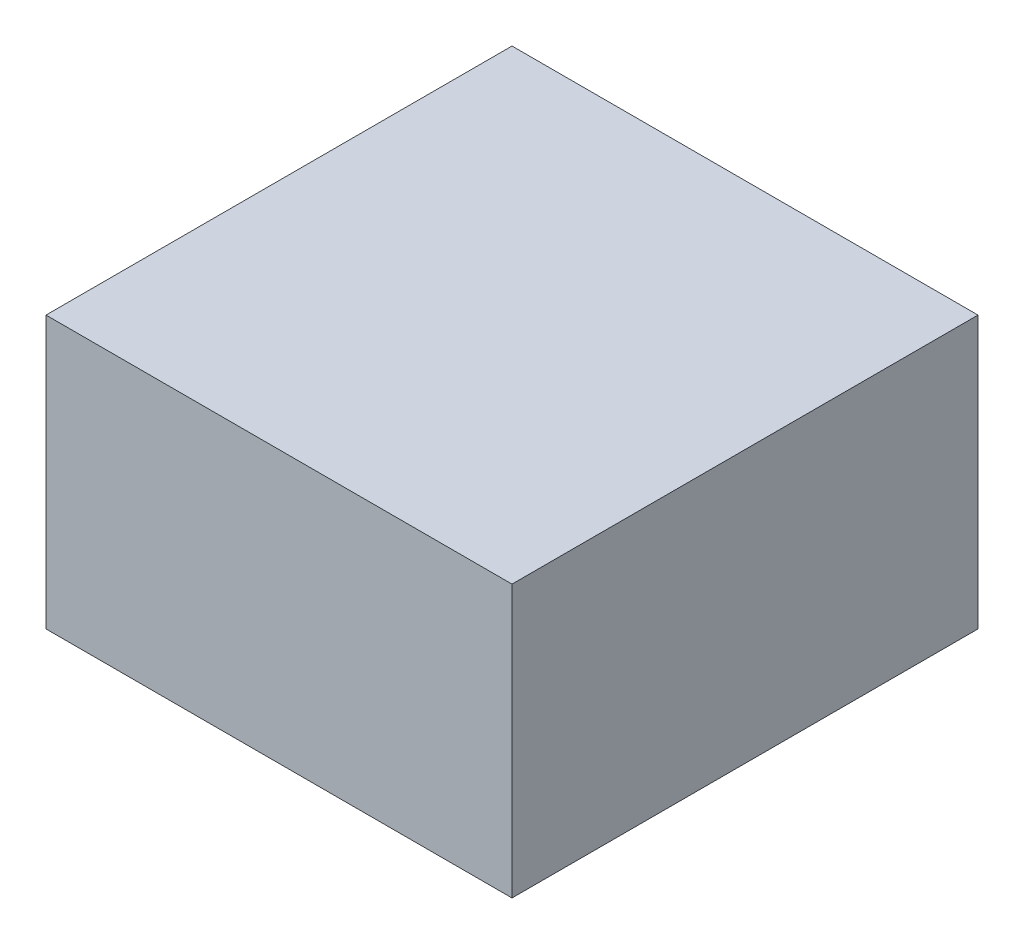
SolidWorks part; units mm, degrees
material "Default"
ref_plane "Front Plane" through (0, 0, 0) normal (0, 0, 1) x (1, 0, 0)
ref_plane "Top Plane" through (0, 0, 0) normal (0, 1, 0) x (1, 0, 0)
ref_plane "Right Plane" through (0, 0, 0) normal (1, 0, 0) x (0, 0, -1)
sketch "Sketch2" plane through (0, 0, 0) normal (0, 1, 0) x (1, 0, 0)
  line L1 (-30, -30) -> (30, -30)
  line L2 (-30, -30) -> (-30, 30)
  line L3 (-30, 30) -> (30, 30)
  line L4 (30, -30) -> (30, 30)
  line L5 (-30, -30) -> (30, 30) construction
  line L6 (-30, 30) -> (30, -30) construction
  point P0 (0, 0)
  dimension "D1" = 60
extrude "Boss-Extrude1" add sketch "Sketch2" along normal blind 35
